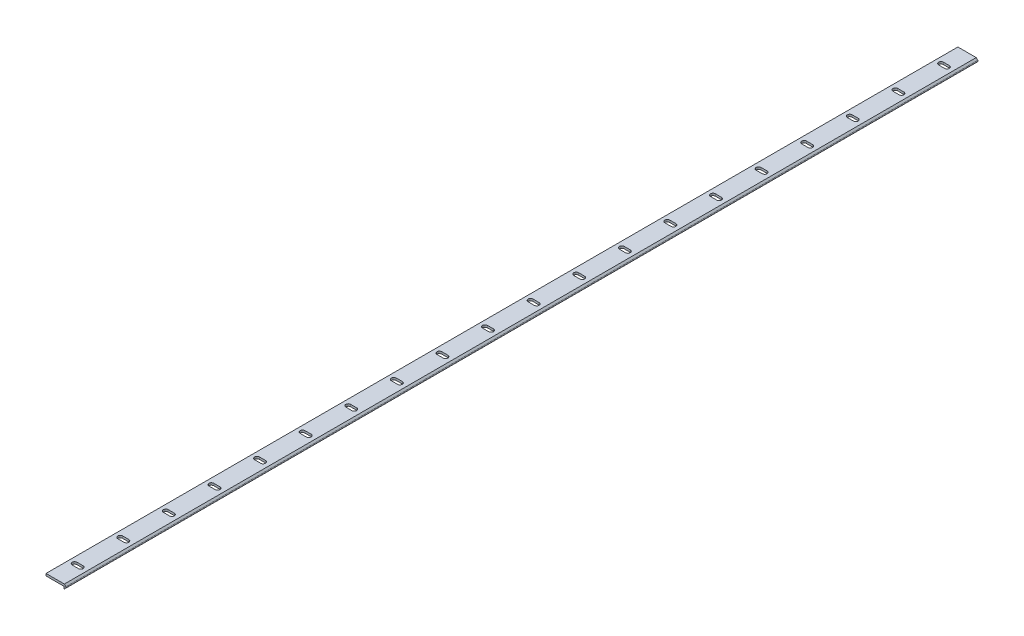
SolidWorks part; units mm, degrees
material "6061-T6 (SS)"
ref_plane "Front Plane" through (0, 0, 0) normal (0, 0, 1) x (1, 0, 0)
ref_plane "Top Plane" through (0, 0, 0) normal (0, 1, 0) x (1, 0, 0)
ref_plane "Right Plane" through (0, 0, 0) normal (1, 0, 0) x (0, 0, -1)
sketch "Sketch1" plane through (0, 0, 0) normal (0, 0, 1) x (1, 0, 0)
  line L0 (19.5291, 0) -> (19.5291, 4.75) construction
  line L1 (0, 0) -> (22.497, 0) construction
  line L2 (0, 0) -> (0, 4.75) construction
  line L3 (0, 4.75) -> (22.497, 4.75) construction
  line L4 (22.497, 0) -> (22.497, 4.75) construction
  line L5 (19.5291, 2.375) -> (0, 2.375)
  line L6 (19.5291, 2.375) -> (19.5291, 0)
  line L7 (19.5291, 4.75) -> (20.122, 4.75)
  line L8 (20.122, 4.75) -> (22.497, 2.375)
  line L9 (19.5291, 4.75) -> (0, 4.75)
  line L10 (0, 4.75) -> (0, 2.375)
  line L11 (22.497, 2.375) -> (20.122, 0)
  line L12 (20.122, 0) -> (19.5291, 0)
  dimension "D1" = 22.497
  dimension "D2" = 4.75
  dimension "D3" = 19.5291
  dimension "D4" = 90
extrude "Boss-Extrude1" add sketch "Sketch1" along normal blind 1000
sketch "Sketch2" plane through (0, 4.75, 0) normal (0, 1, 0) x (1, 0, 0)
  line L0 (0, -1000) -> (0, 0) construction
  line L1 (20.122, 0) -> (0, 0) construction
  line L2 (6.4087, -25) -> (9.7587, -25)
  line L3 (9.7587, -25) -> (13.1087, -25)
  line L4 (6.4087, -22.35) -> (13.1087, -22.35)
  line L5 (13.1087, -27.65) -> (6.4087, -27.65)
  circle A0 centre (9.7587, -25) radius 2.65 construction
  circle A1 centre (13.1087, -25) radius 2.65 construction
  circle A2 centre (6.4087, -25) radius 2.65 construction
  arc A3 (6.4087, -22.35) -> (6.4087, -27.65) centre (6.4087, -25) ccw
  arc A4 (13.1087, -22.35) -> (13.1087, -27.65) centre (13.1087, -25) cw
  point P4 (10.061, 0)
  dimension "D3" = 5.3
  dimension "D1" = 9.7587
  dimension "D2" = 25
  dimension "D4" = 6.7
extrude "Cut-Extrude1" cut sketch "Sketch2" against normal blind 2.375
pattern_linear "LPattern2" count 30 spacing 50 along (0, 0, 1) of "Cut-Extrude1"
fillet "Fillet1" radius 1 1 edges at (22.497, 2.375, 500)
